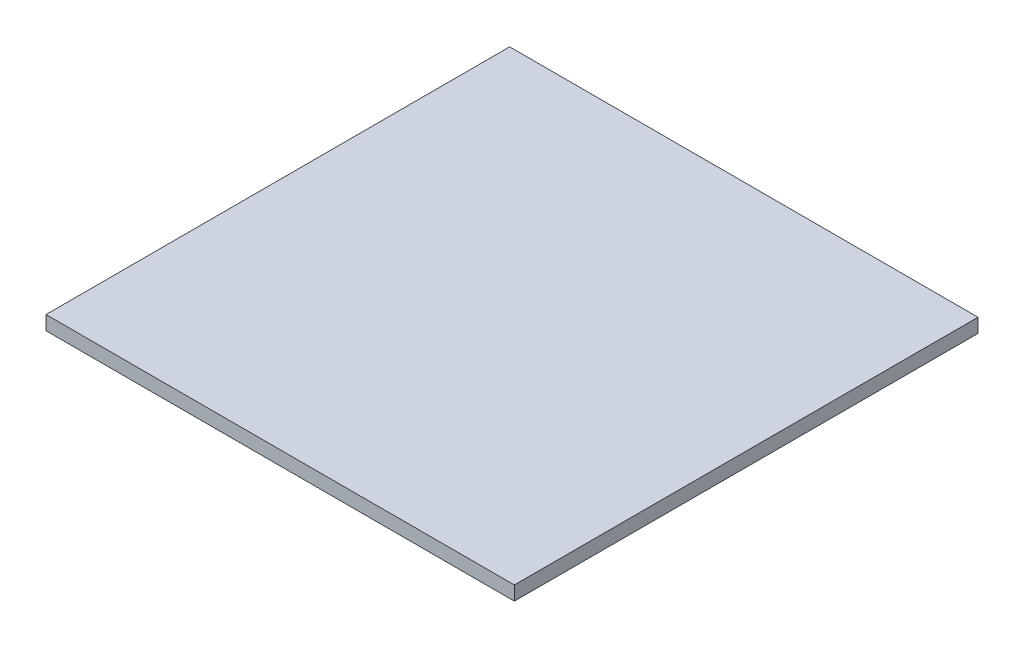
SolidWorks part; units mm, degrees
ref_plane "Спереди" through (0, 0, 0) normal (0, 0, 1) x (1, 0, 0)
ref_plane "Сверху" through (0, 0, 0) normal (0, 1, 0) x (1, 0, 0)
ref_plane "Справа" through (0, 0, 0) normal (1, 0, 0) x (0, 0, -1)
sketch "Эскиз1" plane through (0, 0, 0) normal (0, 1, 0) x (1, 0, 0)
  line L1 (-25, 25) -> (25, 25)
  line L2 (-25, 25) -> (-25, -24.5)
  line L3 (-25, -24.5) -> (25, -24.5)
  line L4 (25, 25) -> (25, -24.5)
  point P0 (0, 0)
extrude "Бобышка-Вытянуть1" add sketch "Эскиз1" along normal blind 1.5
